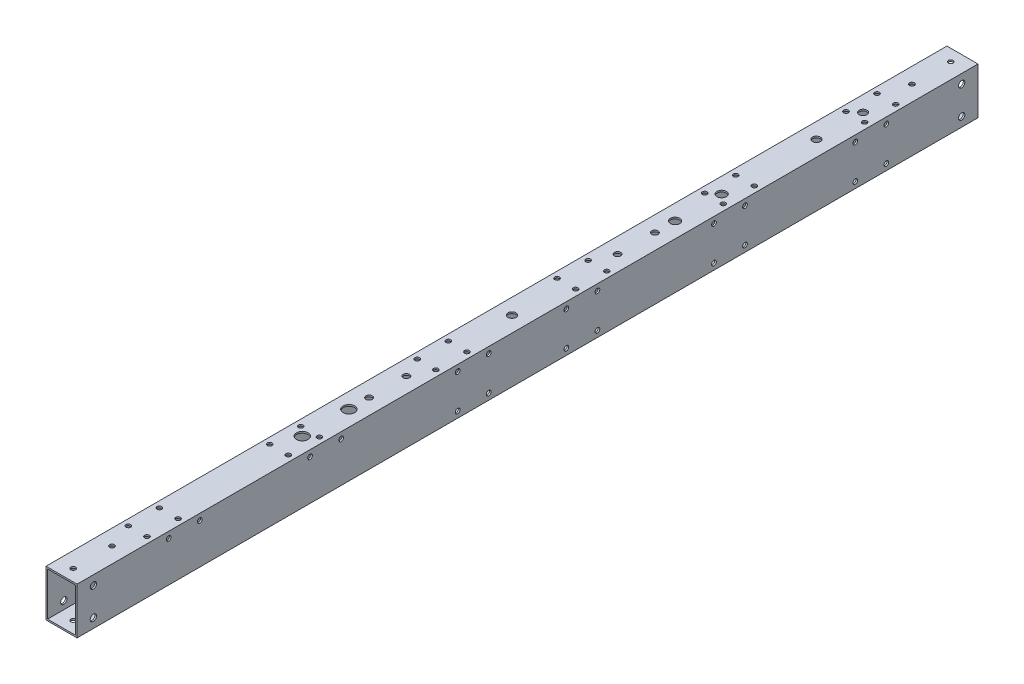
SolidWorks part; units mm, degrees
material "1060 合金"
ref_plane "前视基准面" through (0, 0, 0) normal (0, 0, 1) x (1, 0, 0)
ref_plane "上视基准面" through (0, 0, 0) normal (0, 1, 0) x (1, 0, 0)
ref_plane "右视基准面" through (0, 0, 0) normal (1, 0, 0) x (0, 0, -1)
other "Configuration Table"
sketch "草图1" plane through (0, 0, 0) normal (0, 0, 1) x (1, 0, 0)
  line L0 (-10, -15) -> (-10, 15)
  line L1 (-9, -14) -> (9, -14)
  line L2 (-9, -14) -> (-9, 14)
  line L3 (-9, 14) -> (9, 14)
  line L4 (9, -14) -> (9, 14)
  line L5 (-9, -14) -> (9, 14) construction
  line L6 (-9, 14) -> (9, -14) construction
  line L7 (-10, 15) -> (10, 15)
  line L8 (10, -15) -> (10, 15)
  line L9 (-10, -15) -> (10, -15)
  point P0 (0, 0)
  dimension "D1" = 1
  dimension "D2" = 20
  dimension "D3" = 30
extrude "凸台-拉伸1" add sketch "草图1" along normal mid plane 580
sketch "草图2" plane through (0, -15, 0) normal (0, -1, 0) x (1, 0, 0)
  circle A0 centre (0, 0) radius 5
  dimension "D1" = 10
extrude "切除-拉伸1" cut sketch "草图2" against normal blind 10
sketch "草图3" plane through (0, 14, 0) normal (0, -1, 0) x (1, 0, 0)
  circle A0 centre (0, 0) radius 2.6
  dimension "D1" = 5.2
extrude "切除-拉伸2" cut sketch "草图3" against normal blind 10
sketch "草图4" plane through (0, 15, 0) normal (0, 1, 0) x (1, 0, 0)
  line L0 (0, 290) -> (0, -290) construction
  line L1 (10, 290) -> (-10, 290) construction
  line L2 (10, -290) -> (-10, -290) construction
  line L3 (0, 282.5) -> (0, 257.5) construction
  circle A0 centre (0, 282.5) radius 1.55
  circle A1 centre (0, 257.5) radius 1.55
  dimension "D1" = 3.1
  dimension "D2" = 25
  dimension "D3" = 7.5
extrude "切除-拉伸3" cut sketch "草图4" against normal blind 40
mirror "镜向1" about plane through (0, 0, 0) normal (0, 0, 1) of "切除-拉伸3"
sketch "草图5" plane through (0, 15, 0) normal (0, 1, 0) x (1, 0, 0)
  line L0 (0, 0) -> (0, -50000) construction
  line L1 (0, 100) -> (0, 60) construction
  line L2 (10, 290) -> (-10, 290) construction
  line L3 (0, 92) -> (0, 68) construction
  circle A0 centre (0, 68) radius 2.025
  circle A1 centre (0, 92) radius 2.025
  dimension "D5" = 8
  dimension "D3" = 4.05
  dimension "D1" = 40
  dimension "D2" = 190
  dimension "D4" = 8
extrude "切除-拉伸4" cut sketch "草图5" against normal blind 40
sketch "草图6" plane through (0, -15, 0) normal (0, -1, 0) x (1, 0, 0)
  circle A0 centre (0, -68) radius 3.75
  circle A1 centre (0, -92) radius 3.75
  dimension "D1" = 7.5
extrude "切除-拉伸5" cut sketch "草图6" against normal blind 4
mirror "镜向2" about plane through (0, 0, 0) normal (0, 0, 1) of "切除-拉伸4", "切除-拉伸5"
sketch "草图7" plane through (0, -15, 0) normal (0, -1, 0) x (1, 0, 0)
  line L2 (0, -105) -> (0, -135) construction
  line L3 (0, -105) -> (0, -135) construction
  line L4 (-10, -290) -> (10, -290) construction
  circle A0 centre (0, -105) radius 2.025
  circle A1 centre (0, -135) radius 2.025
  point P9 (0, -120)
  dimension "D4" = 4.05
  dimension "D1" = 170
  dimension "D2" = 30
extrude "切除-拉伸6" cut sketch "草图7" against normal blind 55
sketch "草图9" plane through (0, 15, 0) normal (0, 1, 0) x (1, 0, 0)
  circle A0 centre (0, 105) radius 3
  circle A1 centre (0, 135) radius 3
  dimension "D1" = 6
extrude "切除-拉伸8" cut sketch "草图9" against normal blind 3
sketch "草图10" plane through (0, 15, 0) normal (0, 1, 0) x (1, 0, 0)
  line L0 (0, 290) -> (0, 226) construction
  line L1 (10, 290) -> (-10, 290) construction
  line L2 (0, 226) -> (0, 196) construction
  circle A0 centre (0, 226) radius 2.55
  circle A1 centre (0, 196) radius 2.55
  dimension "D3" = 5.1
  dimension "D1" = 64
  dimension "D2" = 30
extrude "切除-拉伸9" cut sketch "草图10" against normal blind 30
sketch "草图12" plane through (0, 15, 0) normal (0, 1, 0) x (1, 0, 0)
  line L0 (0, 0) -> (0, -120) construction
  line L1 (0, -135) -> (0, -105) construction
  circle A0 centre (0, -105) radius 3.75
  circle A1 centre (0, -135) radius 3.75
  point P6 (0, -120)
  dimension "D4" = 7.5
  dimension "D1" = 120
  dimension "D2" = 15
  dimension "D3" = 30
extrude "切除-拉伸11" cut sketch "草图12" against normal blind 3
sketch "草图13" plane through (0, -14, 0) normal (0, 1, 0) x (1, 0, 0)
  circle A0 centre (0, -105) radius 2.025
  circle A1 centre (0, -135) radius 2.025
  dimension "D1" = 4.05
extrude "切除-拉伸12" cut sketch "草图13" against normal blind 3
sketch "草图14" plane through (-10, 0, 0) normal (-1, 0, 0) x (0, 0, 1)
  line L0 (290, 0) -> (-290, 0) construction
  line L1 (290, 15) -> (290, -15) construction
  line L2 (-290, 15) -> (-290, -15) construction
  line L3 (290, 0) -> (272, 0) construction
  line L4 (264.5, 0) -> (279.5, 0) construction
  line L6 (264.5, -9) -> (279.5, -9) construction
  line L7 (264.5, -9) -> (264.5, 9) construction
  line L8 (264.5, 9) -> (279.5, 9) construction
  line L9 (279.5, -9) -> (279.5, 9) construction
  line L10 (264.5, -9) -> (279.5, 9) construction
  line L11 (264.5, 9) -> (279.5, -9) construction
  line L12 (290, 15) -> (-290, 15) construction
  circle A1 centre (279.5, 9) radius 2.025
  circle A2 centre (279.5, -9) radius 2.025
  circle A4 centre (279.5, 9) radius 3 construction
  point P10 (272, 0)
  dimension "D3" = 4.05
  dimension "D4" = 6
  dimension "D5" = 6
  dimension "D1" = 18
  dimension "D2" = 15
extrude "切除-拉伸13" cut sketch "草图14" against normal blind 30
mirror "镜向3" about plane through (0, 0, 0) normal (0, 0, 1) of "切除-拉伸13"
sketch "草图15" plane through (0, -15, 0) normal (0, -1, 0) x (1, 0, 0)
  line L0 (0, 10) -> (0, -10) construction
  circle A0 centre (0, 10) radius 2.55
  circle A1 centre (0, -10) radius 2.55
  point P6 (0, 0)
  dimension "D1" = 5.1
  dimension "D2" = 20
extrude "切除-拉伸14" cut sketch "草图15" against normal mid plane 10
sketch "草图16" plane through (-10, 0, 0) normal (-1, 0, 0) x (0, 0, 1)
  line L0 (-140, 11) -> (-120, 11) construction
  line L1 (290, 15) -> (-290, 15) construction
  line L2 (-290, 15) -> (-290, -15) construction
  circle A0 centre (-140, 11) radius 1.525
  circle A1 centre (-120, 11) radius 1.525
  dimension "D1" = 4
  dimension "D2" = 3.05
  dimension "D3" = 170
  dimension "D4" = 20
extrude "切除-拉伸15" cut sketch "草图16" against normal blind 40
sketch "草图17" plane through (0, 15, 0) normal (0, 1, 0) x (1, 0, 0)
  line L0 (-6, 150) -> (-6, 130) construction
  line L1 (-10, -290) -> (-10, 290) construction
  line L2 (10, 290) -> (-10, 290) construction
  circle A0 centre (-6, 130) radius 1.525
  circle A1 centre (-6, 150) radius 1.525
  dimension "D1" = 20
  dimension "D4" = 3.05
  dimension "D2" = 4
  dimension "D3" = 140
extrude "切除-拉伸16" cut sketch "草图17" against normal blind 40
mirror "镜向4" about plane through (0, 0, 0) normal (1, 0, 0) of "切除-拉伸15", "切除-拉伸16"
pattern_linear "阵列(线性)1" count 2 spacing 91 along (0, 0, -1) of "切除-拉伸15", "切除-拉伸16", "镜向4"
mirror "镜向7" about plane through (0, 0, 0) normal (0, 0, 1) of "阵列(线性)1", "切除-拉伸15", "切除-拉伸16", "镜向4"
sketch "草图18" plane through (0, 15, 0) normal (0, 1, 0) x (1, 0, 0)
  line L0 (6, 0) -> (6, 55) construction
  line L1 (0, 0) -> (6, 0) construction
  line L3 (10, -290) -> (10, 290) construction
  circle A0 centre (6, 55) radius 1.525
  circle A1 centre (6, 35) radius 1.525
  point P3 (6, 0)
  dimension "D2" = 3.05
  dimension "D3" = 20
  dimension "D4" = 35
  dimension "D1" = 4
extrude "切除-拉伸17" cut sketch "草图18" against normal blind 40
sketch "草图19" plane through (10, 0, 0) normal (1, 0, 0) x (0, 0, -1)
  line L0 (25, 11) -> (45, 11) construction
  line L1 (-290, 15) -> (290, 15) construction
  circle A0 centre (45, 11) radius 1.525
  circle A1 centre (25, 11) radius 1.525
  dimension "D1" = 20
  dimension "D2" = 3.05
  dimension "D4" = 25
  dimension "D3" = 4
extrude "切除-拉伸18" cut sketch "草图19" against normal blind 10
mirror "镜向8" about plane through (0, 0, 0) normal (0, 0, 1) of "切除-拉伸17", "切除-拉伸18" second plane through (0, 0, 0) second plane normal (1, 0, 0)
mirror "镜向9" about plane through (0, 0, 0) normal (0, 1, 0) of "阵列(线性)1", "切除-拉伸15", "镜向8", "切除-拉伸18"
